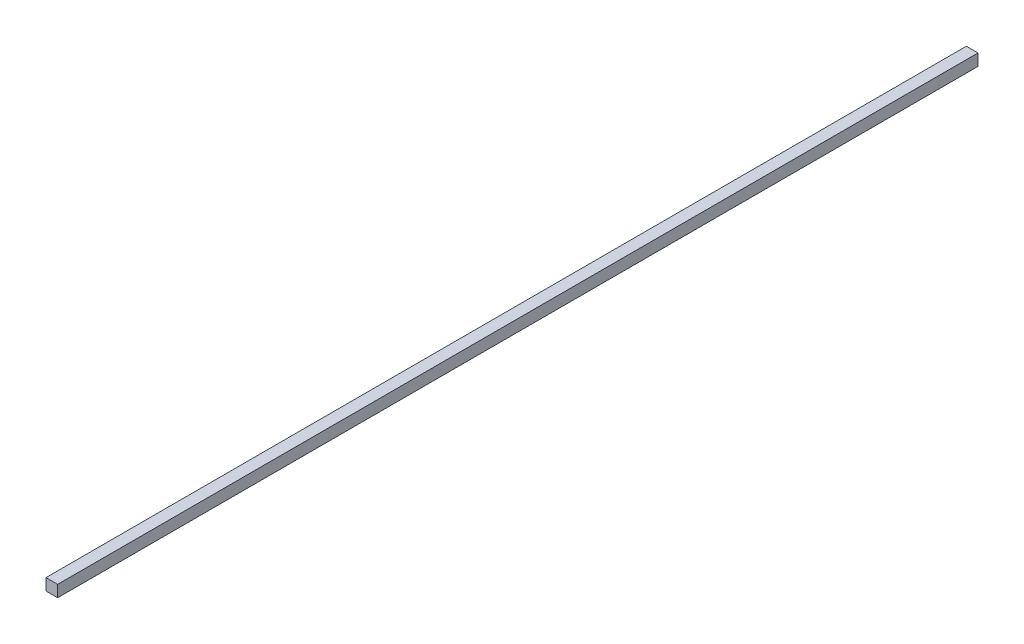
SolidWorks part; units mm, degrees
ref_plane "Front Plane" through (0, 0, 0) normal (0, 0, 1) x (1, 0, 0)
ref_plane "Top Plane" through (0, 0, 0) normal (0, 1, 0) x (1, 0, 0)
ref_plane "Right Plane" through (0, 0, 0) normal (1, 0, 0) x (0, 0, -1)
sketch "Sketch2" plane through (0, 0, 0) normal (0, 0, 1) x (1, 0, 0)
  line L1 (-6.5347, 4.0594) -> (3.4653, 4.0594)
  line L2 (-6.5347, 4.0594) -> (-6.5347, -5.9406)
  line L3 (-6.5347, -5.9406) -> (3.4653, -5.9406)
  line L4 (3.4653, 4.0594) -> (3.4653, -5.9406)
  dimension "D1" = 10
  dimension "D2" = 10
extrude "Boss-Extrude1" add sketch "Sketch2" along normal blind 790
